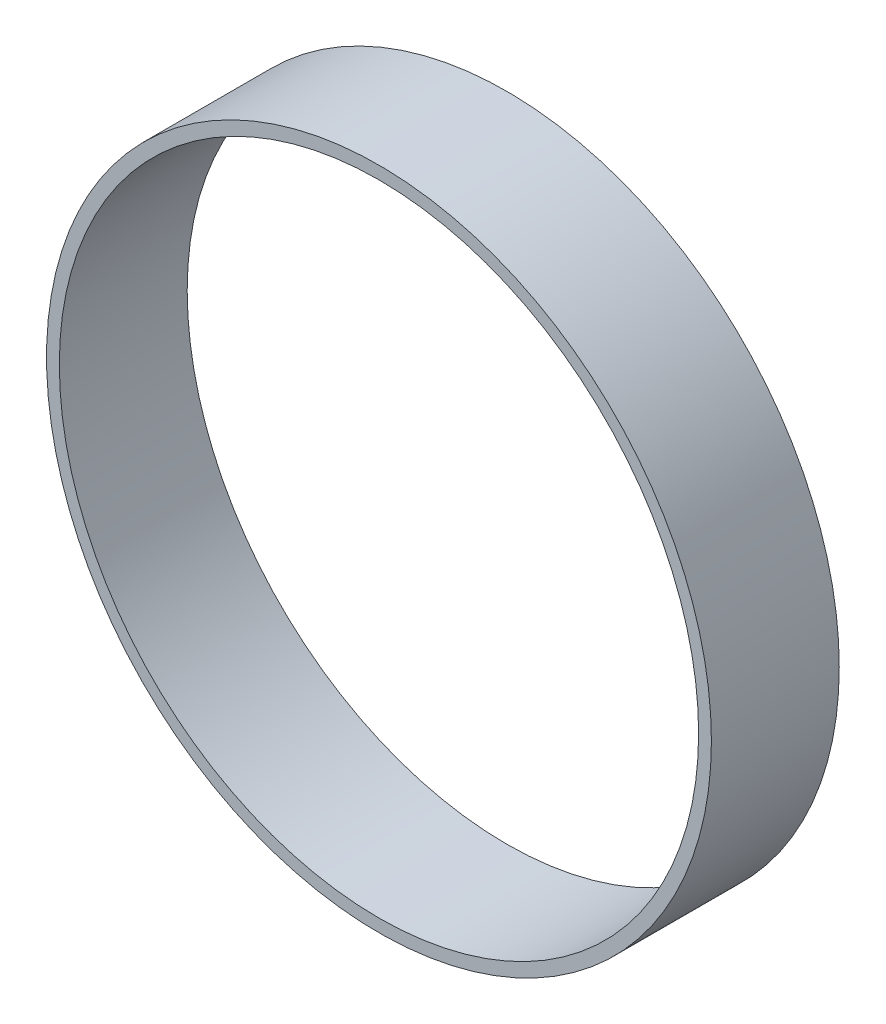
SolidWorks part; units mm, degrees
material "PTFE (general)"
ref_plane "Front Plane" through (0, 0, 0) normal (0, 0, 1) x (1, 0, 0)
ref_plane "Top Plane" through (0, 0, 0) normal (0, 1, 0) x (1, 0, 0)
ref_plane "Right Plane" through (0, 0, 0) normal (1, 0, 0) x (0, 0, -1)
sketch "Sketch2" plane through (0, 0, 0) normal (0, 0, 1) x (1, 0, 0)
  circle A0 centre (0, 0) radius 25
  circle A1 centre (0, 0) radius 26
  dimension "D1" = 50
  dimension "D2" = 52
extrude "Boss-Extrude1" add sketch "Sketch2" along normal blind 10
